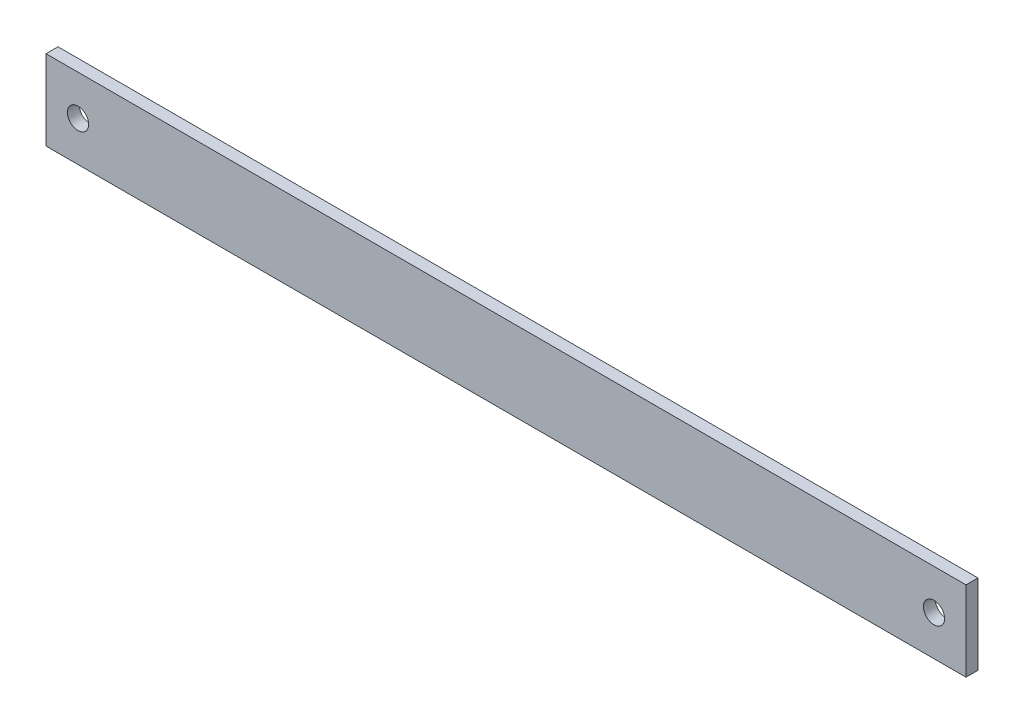
SolidWorks part; units mm, degrees
ref_plane "Front Plane" through (0, 0, 0) normal (0, 0, 1) x (1, 0, 0)
ref_plane "Top Plane" through (0, 0, 0) normal (0, 1, 0) x (1, 0, 0)
ref_plane "Right Plane" through (0, 0, 0) normal (1, 0, 0) x (0, 0, -1)
sketch "Extrusion Base Sketch" plane through (0, 0, 0) normal (0, 0, 1) x (1, 0, 0)
  line L0 (208.75, 17.5) -> (208.75, -2.5)
  line L1 (0, 0) -> (187.5, 0) construction
  line L2 (0, 0) -> (0, 15) construction
  line L3 (0, 15) -> (187.5, 15) construction
  line L4 (187.5, 0) -> (187.5, 15) construction
  line L5 (-21.25, 17.5) -> (208.75, 17.5)
  line L6 (-2.5, 17.5) -> (-2.5, -2.5) construction
  line L7 (-21.25, -2.5) -> (208.75, -2.5)
  line L8 (190, 17.5) -> (190, -2.5) construction
  line L9 (-21.25, 17.5) -> (-21.25, -2.5)
  line L11 (200.75, 7.5) -> (208.75, 7.5) construction
  circle A0 centre (-13.25, 7.5) radius 2.65
  circle A2 centre (200.75, 7.5) radius 2.65
  dimension "D8" = 5.3
  dimension "D1" = 15
  dimension "D2" = 187.5
  dimension "D4" = 2.5
  dimension "D5" = 2.5
  dimension "D6" = 2.5
  dimension "D3" = 20
extrude "Extrusion Base Extrude" add sketch "Extrusion Base Sketch" against normal blind 3
equation "\"Logo Height\"= 15mm"
equation "\"Total Height\"= 20mm"
equation "\"Border\"= ( \"Total Height\" - \"Logo Height\" ) / 2"
equation "\"Text Length\"= 187.5mm"
equation "\"D1@Extrusion Base Sketch\" = \"Logo Height\""
equation "\"D2@Extrusion Base Sketch\" = \"Text Length\""
equation "\"D4@Extrusion Base Sketch\" = \"Border\""
equation "\"D5@Extrusion Base Sketch\" = \"Border\""
equation "\"D6@Extrusion Base Sketch\" = \"Border\""
equation "\"D3@Extrusion Base Sketch\" = \"Total Height\""
